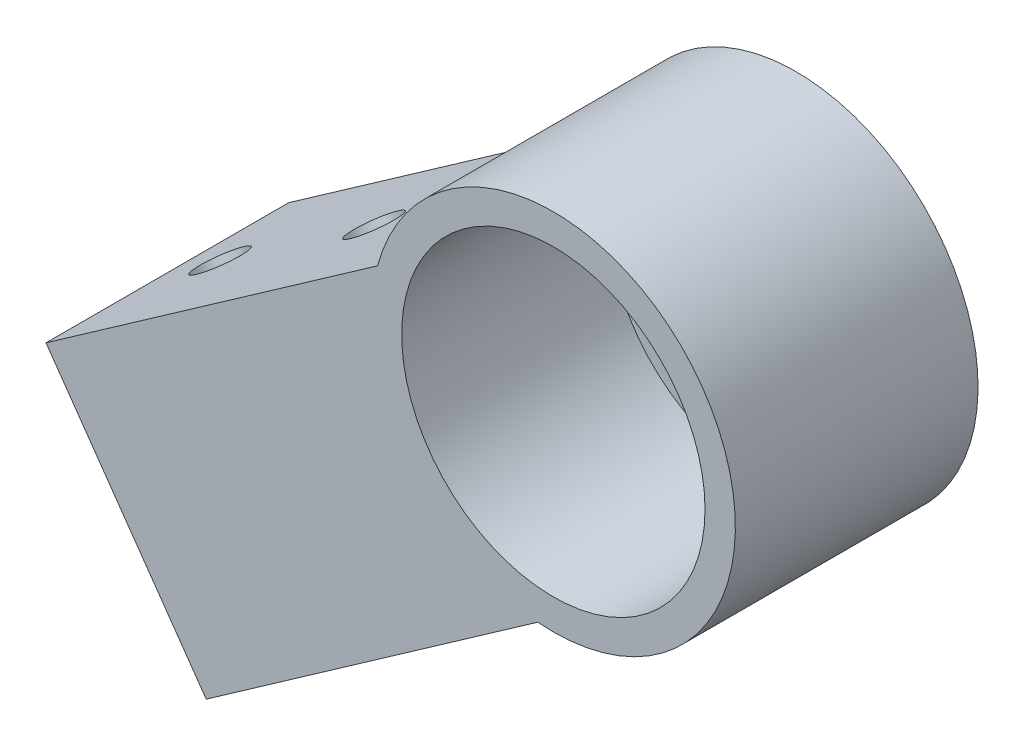
SolidWorks part; units mm, degrees
ref_plane "Front Plane" through (0, 0, 0) normal (0, 0, 1) x (1, 0, 0)
ref_plane "Top Plane" through (0, 0, 0) normal (0, 1, 0) x (1, 0, 0)
ref_plane "Right Plane" through (0, 0, 0) normal (1, 0, 0) x (0, 0, -1)
sketch "Sketch1" plane through (0, 0, 0) normal (0, 0, 1) x (1, 0, 0)
  circle A0 centre (0, 0) radius 15
  dimension "D1" = 30
extrude "Boss-Extrude1" add sketch "Sketch1" along normal blind 3
sketch "Sketch2" plane through (0, 0, 3) normal (0, 0, 1) x (1, 0, 0)
  circle A0 centre (0, 0) radius 15
  circle A1 centre (0, 0) radius 12.5
  dimension "D1" = 25
extrude "Boss-Extrude2" add sketch "Sketch2" along normal blind 17
sketch "Sketch3" plane through (0, 0, 3) normal (0, 0, 1) x (1, 0, 0)
  circle A0 centre (0, 0) radius 3
  circle A1 centre (-6.9602, -4.8791) radius 1.5
  circle A2 centre (6.9602, 4.8791) radius 1.5
  arc A5 (-5.9367, -4.1616) -> (-7.9838, -5.5966) centre (-6.9602, -4.8791) ccw construction
  arc A6 (7.9838, 5.5966) -> (5.9367, 4.1616) centre (6.9602, 4.8791) ccw construction
  dimension "D1" = 3
  dimension "D2" = 3
extrude "Cut-Extrude1" cut sketch "Sketch3" against normal up to surface (3 mm away) up to face at (15, 0, 0)
sketch "Sketch4" plane through (0, 0, 0) normal (0, 0, -1) x (-1, 0, 0)
  line L0 (-6.9602, 4.8791) -> (16.5772, -11.6205) construction
  line L1 (14.4872, 3.8887) -> (41.8116, -15.2656)
  line L2 (41.8116, -15.2656) -> (28.6094, -34.0991)
  line L3 (28.6094, -34.0991) -> (1.285, -14.9449)
  circle A1 centre (0, 0) radius 15 construction
  arc A2 (14.4872, 3.8887) -> (1.285, -14.9449) centre (0, 0) cw
  dimension "D1" = 11.5
  dimension "D2" = 11.5
  dimension "D3" = 28
extrude "Boss-Extrude3" add sketch "Sketch4" against normal up to surface (20 mm away) up to face at (15, 0, 20)
sketch "Sketch6" plane through (-35.2105, -24.6823, 0) normal (-0.8188, -0.574, 0) x (-0.574, 0.8188, 0)
  line L0 (-11.5, -20) -> (11.5, 0) construction
  line L2 (-6.5, -3.5) -> (6.5, -3.5)
  line L3 (-6.5, -3.5) -> (-6.5, -16.5)
  line L4 (-6.5, -16.5) -> (6.5, -16.5)
  line L5 (6.5, -3.5) -> (6.5, -16.5)
  line L6 (-6.5, -3.5) -> (6.5, -16.5) construction
  line L7 (-6.5, -16.5) -> (6.5, -3.5) construction
  point P4 (0, -10)
  dimension "D1" = 13
  dimension "D2" = 13
extrude "Cut-Extrude3" cut sketch "Sketch6" against normal blind 26
sketch "Sketch7" plane through (6.6011, -9.4168, 0) normal (0.574, -0.8188, 0) x (0, 0, 1)
  circle A0 centre (10, 37.7) radius 2
  circle A1 centre (10, 22.2) radius 2
  dimension "D1" = 4
extrude "Cut-Extrude4" cut sketch "Sketch7" against normal through all
